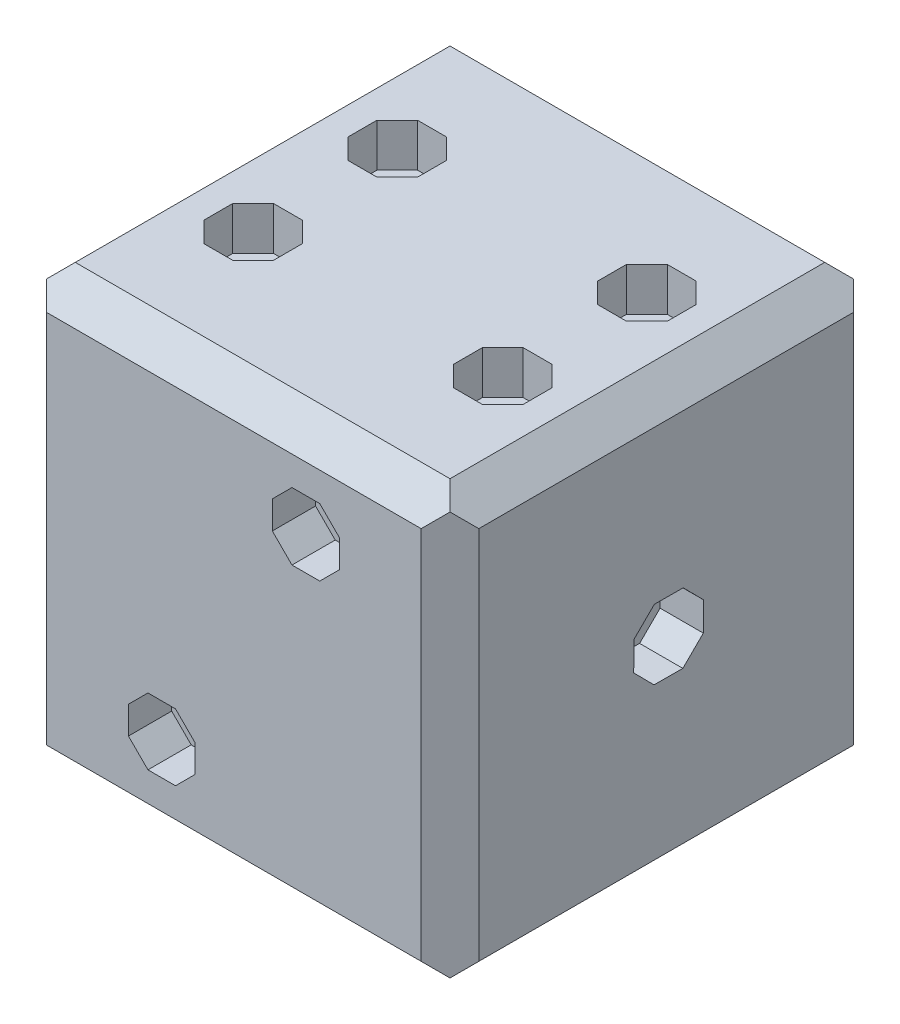
SolidWorks part; units mm, degrees
ref_plane "Front Plane" through (0, 0, 0) normal (0, 0, 1) x (1, 0, 0)
ref_plane "Top Plane" through (0, 0, 0) normal (0, 1, 0) x (1, 0, 0)
ref_plane "Right Plane" through (0, 0, 0) normal (1, 0, 0) x (0, 0, -1)
sketch "Sketch1" plane through (0, 0, 0) normal (0, 1, 0) x (1, 0, 0)
  line L1 (-7.5, 7.5) -> (7.5, 7.5)
  line L2 (-7.5, 7.5) -> (-7.5, -7.5)
  line L3 (-7.5, -7.5) -> (7.5, -7.5)
  line L4 (7.5, 7.5) -> (7.5, -7.5)
  line L5 (-7.5, 7.5) -> (7.5, -7.5) construction
  line L6 (-7.5, -7.5) -> (7.5, 7.5) construction
  point P0 (0, 0)
extrude "Boss-Extrude1" add sketch "Sketch1" along normal blind 15
sketch "Sketch2" plane through (7.5, 0, 0) normal (1, 0, 0) x (0, 0, -1)
  line L1 (-0.4228, 6.2685) -> (0.5772, 6.2635)
  line L2 (0.5772, 6.2635) -> (1.2879, 6.9671)
  line L3 (1.2879, 6.9671) -> (1.2929, 7.9671)
  line L4 (1.2929, 7.9671) -> (0.5893, 8.6777)
  line L5 (0.5893, 8.6777) -> (-0.4107, 8.6827)
  line L6 (-0.4107, 8.6827) -> (-1.1213, 7.9791)
  line L7 (-1.1213, 7.9791) -> (-1.1263, 6.9791)
  line L8 (-1.1263, 6.9791) -> (-0.4228, 6.2685)
  circle A0 centre (0.0833, 7.4731) radius 1.2071 construction
sketch "Sketch3" plane through (0, 15, 0) normal (0, 1, 0) x (1, 0, 0)
  line L1 (4.3301, -2.5) -> (4.3301, 2.5)
  line L2 (4.3301, 2.5) -> (0, 5)
  line L3 (0, 5) -> (-4.3301, 2.5)
  line L4 (-4.3301, 2.5) -> (-4.3301, -2.5)
  line L5 (-4.3301, -2.5) -> (0, -5)
  line L6 (0, -5) -> (4.3301, -2.5)
  circle A0 centre (0, 0) radius 5 construction
sketch "Sketch4" plane through (-7.5, 0, 0) normal (-1, 0, 0) x (0, 0, 1)
  line L1 (2.5, 11.8301) -> (-2.5, 11.8301)
  line L2 (-2.5, 11.8301) -> (-5, 7.5)
  line L3 (-5, 7.5) -> (-2.5, 3.1699)
  line L4 (-2.5, 3.1699) -> (2.5, 3.1699)
  line L5 (2.5, 3.1699) -> (5, 7.5)
  line L6 (5, 7.5) -> (2.5, 11.8301)
  circle A0 centre (0, 7.5) radius 5 construction
sketch "Sketch5" plane through (0, 0, 0) normal (0, -1, 0) x (1, 0, 0)
  line L1 (0, 5) -> (-4.3301, 2.5)
  line L2 (-4.3301, 2.5) -> (-4.3301, -2.5)
  line L3 (-4.3301, -2.5) -> (0, -5)
  line L4 (0, -5) -> (4.3301, -2.5)
  line L5 (4.3301, -2.5) -> (4.3301, 2.5)
  line L6 (4.3301, 2.5) -> (0, 5)
  circle A0 centre (0, 0) radius 5 construction
sketch "Sketch6" plane through (0, 0, -7.5) normal (0, 0, -1) x (-1, 0, 0)
  line L1 (2.5, 11.8301) -> (-2.5, 11.8301)
  line L2 (-2.5, 11.8301) -> (-5, 7.5)
  line L3 (-5, 7.5) -> (-2.5, 3.1699)
  line L4 (-2.5, 3.1699) -> (2.5, 3.1699)
  line L5 (2.5, 3.1699) -> (5, 7.5)
  line L6 (5, 7.5) -> (2.5, 11.8301)
  circle A0 centre (0, 7.5) radius 5 construction
sketch "Sketch7" plane through (7.5, 0, 0) normal (1, 0, 0) x (0, 0, -1)
  line L1 (2.5, 11.8301) -> (-2.5, 11.8301)
  line L2 (-2.5, 11.8301) -> (-5, 7.5)
  line L3 (-5, 7.5) -> (-2.5, 3.1699)
  line L4 (-2.5, 3.1699) -> (2.5, 3.1699)
  line L5 (2.5, 3.1699) -> (5, 7.5)
  line L6 (5, 7.5) -> (2.5, 11.8301)
  circle A0 centre (0, 7.5) radius 5 construction
sketch "Sketch8" plane through (0, 0, 7.5) normal (0, 0, 1) x (1, 0, 0)
  line L1 (2.5, 11.8301) -> (-2.5, 11.8301)
  line L2 (-2.5, 11.8301) -> (-5, 7.5)
  line L3 (-5, 7.5) -> (-2.5, 3.1699)
  line L4 (-2.5, 3.1699) -> (2.5, 3.1699)
  line L5 (2.5, 3.1699) -> (5, 7.5)
  line L6 (5, 7.5) -> (2.5, 11.8301)
  circle A0 centre (0, 7.5) radius 5 construction
extrude "Cut-Extrude2" cut sketch "Sketch2" against normal blind 1.5
sketch "Sketch9" plane through (0, 0, 7.5) normal (0, 0, 1) x (1, 0, 0)
  line L1 (2.9821, 10.6663) -> (3.6638, 11.3481)
  line L2 (3.6638, 11.3481) -> (3.6638, 12.3122)
  line L3 (3.6638, 12.3122) -> (2.9821, 12.994)
  line L4 (2.9821, 12.994) -> (2.0179, 12.994)
  line L5 (2.0179, 12.994) -> (1.3362, 12.3122)
  line L6 (1.3362, 12.3122) -> (1.3362, 11.3481)
  line L7 (1.3362, 11.3481) -> (2.0179, 10.6663)
  line L8 (2.0179, 10.6663) -> (2.9821, 10.6663)
  circle A0 centre (2.5, 11.8301) radius 1.2597 construction
sketch "Sketch10" plane through (0, 0, 7.5) normal (0, 0, 1) x (1, 0, 0)
  line L1 (-2.9784, 4.3247) -> (-3.6548, 3.6482)
  line L2 (-3.6548, 3.6482) -> (-3.6548, 2.6915)
  line L3 (-3.6548, 2.6915) -> (-2.9784, 2.015)
  line L4 (-2.9784, 2.015) -> (-2.0216, 2.015)
  line L5 (-2.0216, 2.015) -> (-1.3452, 2.6915)
  line L6 (-1.3452, 2.6915) -> (-1.3452, 3.6482)
  line L7 (-1.3452, 3.6482) -> (-2.0216, 4.3247)
  line L8 (-2.0216, 4.3247) -> (-2.9784, 4.3247)
  circle A0 centre (-2.5, 3.1699) radius 1.25 construction
extrude "Cut-Extrude3" cut sketch "Sketch9" against normal blind 1.5
extrude "Cut-Extrude4" cut sketch "Sketch10" against normal blind 1.5
sketch "Sketch12" plane through (0, 0, 0) normal (0, -1, 0) x (-1, 0, 0)
  line L1 (-5.5372, -3) -> (-4.8301, -3.7071)
  line L2 (-4.8301, -3.7071) -> (-3.8301, -3.7071)
  line L3 (-3.8301, -3.7071) -> (-3.123, -3)
  line L4 (-3.123, -3) -> (-3.123, -2)
  line L5 (-3.123, -2) -> (-3.8301, -1.2929)
  line L6 (-3.8301, -1.2929) -> (-4.8301, -1.2929)
  line L7 (-4.8301, -1.2929) -> (-5.5372, -2)
  line L8 (-5.5372, -2) -> (-5.5372, -3)
  circle A0 centre (-4.3301, -2.5) radius 1.3066 construction
sketch "Sketch13" plane through (0, 0, 0) normal (0, -1, 0) x (-1, 0, 0)
  line L1 (3.8301, -3.7071) -> (4.8301, -3.7071)
  line L2 (4.8301, -3.7071) -> (5.5372, -3)
  line L3 (5.5372, -3) -> (5.5372, -2)
  line L4 (5.5372, -2) -> (4.8301, -1.2929)
  line L5 (4.8301, -1.2929) -> (3.8301, -1.2929)
  line L6 (3.8301, -1.2929) -> (3.123, -2)
  line L7 (3.123, -2) -> (3.123, -3)
  line L8 (3.123, -3) -> (3.8301, -3.7071)
  circle A0 centre (4.3301, -2.5) radius 1.3066 construction
sketch "Sketch14" plane through (0, 0, 0) normal (0, -1, 0) x (-1, 0, 0)
  line L1 (0.5, 3.7929) -> (1.2071, 4.5)
  line L2 (1.2071, 4.5) -> (1.2071, 5.5)
  line L3 (1.2071, 5.5) -> (0.5, 6.2071)
  line L4 (0.5, 6.2071) -> (-0.5, 6.2071)
  line L5 (-0.5, 6.2071) -> (-1.2071, 5.5)
  line L6 (-1.2071, 5.5) -> (-1.2071, 4.5)
  line L7 (-1.2071, 4.5) -> (-0.5, 3.7929)
  line L8 (-0.5, 3.7929) -> (0.5, 3.7929)
  circle A0 centre (0, 5) radius 1.3066 construction
extrude "Cut-Extrude5" cut sketch "Sketch12" against normal blind 1.5
extrude "Cut-Extrude6" cut sketch "Sketch13" against normal blind 1.5
extrude "Cut-Extrude7" cut sketch "Sketch14" against normal blind 1.5
sketch "Sketch15" plane through (0, 15, 0) normal (0, 1, 0) x (1, 0, 0)
  line L1 (4.8301, -3.7071) -> (5.5372, -3)
  line L2 (5.5372, -3) -> (5.5372, -2)
  line L3 (5.5372, -2) -> (4.8301, -1.2929)
  line L4 (4.8301, -1.2929) -> (3.8301, -1.2929)
  line L5 (3.8301, -1.2929) -> (3.123, -2)
  line L6 (3.123, -2) -> (3.123, -3)
  line L7 (3.123, -3) -> (3.8301, -3.7071)
  line L8 (3.8301, -3.7071) -> (4.8301, -3.7071)
  circle A0 centre (4.3301, -2.5) radius 1.2071 construction
sketch "Sketch16" plane through (0, 15, 0) normal (0, 1, 0) x (1, 0, 0)
  line L1 (4.8301, 1.2929) -> (5.5372, 2)
  line L2 (5.5372, 2) -> (5.5372, 3)
  line L3 (5.5372, 3) -> (4.8301, 3.7071)
  line L4 (4.8301, 3.7071) -> (3.8301, 3.7071)
  line L5 (3.8301, 3.7071) -> (3.123, 3)
  line L6 (3.123, 3) -> (3.123, 2)
  line L7 (3.123, 2) -> (3.8301, 1.2929)
  line L8 (3.8301, 1.2929) -> (4.8301, 1.2929)
  circle A0 centre (4.3301, 2.5) radius 1.2071 construction
sketch "Sketch17" plane through (0, 15, 0) normal (0, 1, 0) x (1, 0, 0)
  line L1 (-3.8301, 1.2929) -> (-3.123, 2)
  line L2 (-3.123, 2) -> (-3.123, 3)
  line L3 (-3.123, 3) -> (-3.8301, 3.7071)
  line L4 (-3.8301, 3.7071) -> (-4.8301, 3.7071)
  line L5 (-4.8301, 3.7071) -> (-5.5372, 3)
  line L6 (-5.5372, 3) -> (-5.5372, 2)
  line L7 (-5.5372, 2) -> (-4.8301, 1.2929)
  line L8 (-4.8301, 1.2929) -> (-3.8301, 1.2929)
  circle A0 centre (-4.3301, 2.5) radius 1.2071 construction
sketch "Sketch18" plane through (0, 15, 0) normal (0, 1, 0) x (1, 0, 0)
  line L1 (-4.8301, -1.2929) -> (-5.5372, -2)
  line L2 (-5.5372, -2) -> (-5.5372, -3)
  line L3 (-5.5372, -3) -> (-4.8301, -3.7071)
  line L4 (-4.8301, -3.7071) -> (-3.8301, -3.7071)
  line L5 (-3.8301, -3.7071) -> (-3.123, -3)
  line L6 (-3.123, -3) -> (-3.123, -2)
  line L7 (-3.123, -2) -> (-3.8301, -1.2929)
  line L8 (-3.8301, -1.2929) -> (-4.8301, -1.2929)
  circle A0 centre (-4.3301, -2.5) radius 1.2071 construction
sketch "Sketch19" plane through (-7.5, 0, 0) normal (-1, 0, 0) x (0, 0, 1)
  line L1 (3, 4.377) -> (2, 4.377)
  line L2 (2, 4.377) -> (1.2929, 3.6699)
  line L3 (1.2929, 3.6699) -> (1.2929, 2.6699)
  line L4 (1.2929, 2.6699) -> (2, 1.9628)
  line L5 (2, 1.9628) -> (3, 1.9628)
  line L6 (3, 1.9628) -> (3.7071, 2.6699)
  line L7 (3.7071, 2.6699) -> (3.7071, 3.6699)
  line L8 (3.7071, 3.6699) -> (3, 4.377)
  circle A0 centre (2.5, 3.1699) radius 1.2071 construction
sketch "Sketch20" plane through (-7.5, 0, 0) normal (-1, 0, 0) x (0, 0, 1)
  line L1 (5.5, 6.2929) -> (6.2071, 7)
  line L2 (6.2071, 7) -> (6.2071, 8)
  line L3 (6.2071, 8) -> (5.5, 8.7071)
  line L4 (5.5, 8.7071) -> (4.5, 8.7071)
  line L5 (4.5, 8.7071) -> (3.7929, 8)
  line L6 (3.7929, 8) -> (3.7929, 7)
  line L7 (3.7929, 7) -> (4.5, 6.2929)
  line L8 (4.5, 6.2929) -> (5.5, 6.2929)
  circle A0 centre (5, 7.5) radius 1.2071 construction
sketch "Sketch21" plane through (-7.5, 0, 0) normal (-1, 0, 0) x (0, 0, 1)
  line L1 (2, 13.0372) -> (1.2929, 12.3301)
  line L2 (1.2929, 12.3301) -> (1.2929, 11.3301)
  line L3 (1.2929, 11.3301) -> (2, 10.623)
  line L4 (2, 10.623) -> (3, 10.623)
  line L5 (3, 10.623) -> (3.7071, 11.3301)
  line L6 (3.7071, 11.3301) -> (3.7071, 12.3301)
  line L7 (3.7071, 12.3301) -> (3, 13.0372)
  line L8 (3, 13.0372) -> (2, 13.0372)
  circle A0 centre (2.5, 11.8301) radius 1.2071 construction
sketch "Sketch22" plane through (-7.5, 0, 0) normal (-1, 0, 0) x (0, 0, 1)
  line L1 (-2, 1.9628) -> (-1.2929, 2.6699)
  line L2 (-1.2929, 2.6699) -> (-1.2929, 3.6699)
  line L3 (-1.2929, 3.6699) -> (-2, 4.377)
  line L4 (-2, 4.377) -> (-3, 4.377)
  line L5 (-3, 4.377) -> (-3.7071, 3.6699)
  line L6 (-3.7071, 3.6699) -> (-3.7071, 2.6699)
  line L7 (-3.7071, 2.6699) -> (-3, 1.9628)
  line L8 (-3, 1.9628) -> (-2, 1.9628)
  circle A0 centre (-2.5, 3.1699) radius 1.2071 construction
sketch "Sketch23" plane through (-7.5, 0, 0) normal (-1, 0, 0) x (0, 0, 1)
  line L1 (-4.5, 6.2929) -> (-3.7929, 7)
  line L2 (-3.7929, 7) -> (-3.7929, 8)
  line L3 (-3.7929, 8) -> (-4.5, 8.7071)
  line L4 (-4.5, 8.7071) -> (-5.5, 8.7071)
  line L5 (-5.5, 8.7071) -> (-6.2071, 8)
  line L6 (-6.2071, 8) -> (-6.2071, 7)
  line L7 (-6.2071, 7) -> (-5.5, 6.2929)
  line L8 (-5.5, 6.2929) -> (-4.5, 6.2929)
  circle A0 centre (-5, 7.5) radius 1.2071 construction
sketch "Sketch24" plane through (-7.5, 0, 0) normal (-1, 0, 0) x (0, 0, 1)
  line L1 (-2, 10.623) -> (-1.2929, 11.3301)
  line L2 (-1.2929, 11.3301) -> (-1.2929, 12.3301)
  line L3 (-1.2929, 12.3301) -> (-2, 13.0372)
  line L4 (-2, 13.0372) -> (-3, 13.0372)
  line L5 (-3, 13.0372) -> (-3.7071, 12.3301)
  line L6 (-3.7071, 12.3301) -> (-3.7071, 11.3301)
  line L7 (-3.7071, 11.3301) -> (-3, 10.623)
  line L8 (-3, 10.623) -> (-2, 10.623)
  circle A0 centre (-2.5, 11.8301) radius 1.2071 construction
sketch "Sketch25" plane through (0, 0, -7.5) normal (0, 0, -1) x (-1, 0, 0)
  line L1 (-1.975, 1.9023) -> (-1.2324, 2.6448)
  line L2 (-1.2324, 2.6448) -> (-1.2324, 3.6949)
  line L3 (-1.2324, 3.6949) -> (-1.975, 4.4374)
  line L4 (-1.975, 4.4374) -> (-3.025, 4.4374)
  line L5 (-3.025, 4.4374) -> (-3.7676, 3.6949)
  line L6 (-3.7676, 3.6949) -> (-3.7676, 2.6448)
  line L7 (-3.7676, 2.6448) -> (-3.025, 1.9023)
  line L8 (-3.025, 1.9023) -> (-1.975, 1.9023)
  circle A0 centre (-2.5, 3.1699) radius 1.2676 construction
sketch "Sketch26" plane through (0, 0, -7.5) normal (0, 0, -1) x (-1, 0, 0)
  line L1 (3, 1.9628) -> (3.7071, 2.6699)
  line L2 (3.7071, 2.6699) -> (3.7071, 3.6699)
  line L3 (3.7071, 3.6699) -> (3, 4.377)
  line L4 (3, 4.377) -> (2, 4.377)
  line L5 (2, 4.377) -> (1.2929, 3.6699)
  line L6 (1.2929, 3.6699) -> (1.2929, 2.6699)
  line L7 (1.2929, 2.6699) -> (2, 1.9628)
  line L8 (2, 1.9628) -> (3, 1.9628)
  circle A0 centre (2.5, 3.1699) radius 1.2071 construction
sketch "Sketch27" plane through (0, 0, -7.5) normal (0, 0, -1) x (-1, 0, 0)
  line L1 (5.5, 6.2929) -> (6.2071, 7)
  line L2 (6.2071, 7) -> (6.2071, 8)
  line L3 (6.2071, 8) -> (5.5, 8.7071)
  line L4 (5.5, 8.7071) -> (4.5, 8.7071)
  line L5 (4.5, 8.7071) -> (3.7929, 8)
  line L6 (3.7929, 8) -> (3.7929, 7)
  line L7 (3.7929, 7) -> (4.5, 6.2929)
  line L8 (4.5, 6.2929) -> (5.5, 6.2929)
  circle A0 centre (5, 7.5) radius 1.2071 construction
sketch "Sketch28" plane through (0, 0, -7.5) normal (0, 0, -1) x (-1, 0, 0)
  line L1 (3.0887, 10.4088) -> (3.9213, 11.2414)
  line L2 (3.9213, 11.2414) -> (3.9213, 12.4188)
  line L3 (3.9213, 12.4188) -> (3.0887, 13.2514)
  line L4 (3.0887, 13.2514) -> (1.9113, 13.2514)
  line L5 (1.9113, 13.2514) -> (1.0787, 12.4188)
  line L6 (1.0787, 12.4188) -> (1.0787, 11.2414)
  line L7 (1.0787, 11.2414) -> (1.9113, 10.4088)
  line L8 (1.9113, 10.4088) -> (3.0887, 10.4088)
  circle A0 centre (2.5, 11.8301) radius 1.4213 construction
sketch "Sketch29" plane through (0, 0, -7.5) normal (0, 0, -1) x (-1, 0, 0)
  line L1 (-2, 10.623) -> (-1.2929, 11.3301)
  line L2 (-1.2929, 11.3301) -> (-1.2929, 12.3301)
  line L3 (-1.2929, 12.3301) -> (-2, 13.0372)
  line L4 (-2, 13.0372) -> (-3, 13.0372)
  line L5 (-3, 13.0372) -> (-3.7071, 12.3301)
  line L6 (-3.7071, 12.3301) -> (-3.7071, 11.3301)
  line L7 (-3.7071, 11.3301) -> (-3, 10.623)
  line L8 (-3, 10.623) -> (-2, 10.623)
  circle A0 centre (-2.5, 11.8301) radius 1.2071 construction
extrude "Cut-Extrude8" cut sketch "Sketch29" against normal blind 1.5
extrude "Cut-Extrude9" cut sketch "Sketch28" against normal blind 1.5
extrude "Cut-Extrude10" cut sketch "Sketch27" against normal blind 1.5
extrude "Cut-Extrude11" cut sketch "Sketch26" against normal blind 1.5
extrude "Cut-Extrude12" cut sketch "Sketch25" against normal blind 1.5
extrude "Cut-Extrude13" cut sketch "Sketch24" against normal blind 1.5
extrude "Cut-Extrude14" cut sketch "Sketch23" against normal blind 1.5
extrude "Cut-Extrude15" cut sketch "Sketch22" against normal blind 1.5
extrude "Cut-Extrude16" cut sketch "Sketch21" against normal blind 1.5
extrude "Cut-Extrude17" cut sketch "Sketch20" against normal blind 1.5
extrude "Cut-Extrude18" cut sketch "Sketch19" against normal blind 1.5
extrude "Cut-Extrude19" cut sketch "Sketch18" against normal blind 1.5
extrude "Cut-Extrude20" cut sketch "Sketch17" against normal blind 1.5
extrude "Cut-Extrude21" cut sketch "Sketch16" against normal blind 1.5
extrude "Cut-Extrude22" cut sketch "Sketch15" against normal blind 1.5
chamfer "Chamfer1" distance 1 angle 45 1 edges at (-7.5, 7.5, 7.5)
chamfer "Chamfer2" distance 1 angle 45 1 edges at (-7.5, 0, -0.5)
chamfer "Chamfer3" distance 1 angle 45 1 edges at (0.5, 0, 7.5)
chamfer "Chamfer4" distance 1 angle 45 1 edges at (0.5, 15, 7.5)
chamfer "Chamfer5" distance 1 angle 45 1 edges at (-7.5, 15, -0.5)
chamfer "Chamfer6" distance 1 angle 45 1 edges at (-7.5, 7.5, -7.5)
chamfer "Chamfer7" distance 1 angle 45 1 edges at (0.5, 15, -7.5)
chamfer "Chamfer8" distance 1 angle 45 1 edges at (0.5, 0, -7.5)
chamfer "Chamfer9" distance 1 angle 45 1 edges at (7.5, 7.5, 7.5)
chamfer "Chamfer10" distance 1 angle 45 1 edges at (7.5, 15, 0)
chamfer "Chamfer11" distance 1 angle 45 1 edges at (7.5, 7.5, -7.5)
chamfer "Chamfer12" distance 1 angle 45 1 edges at (7.5, 0, 0)
